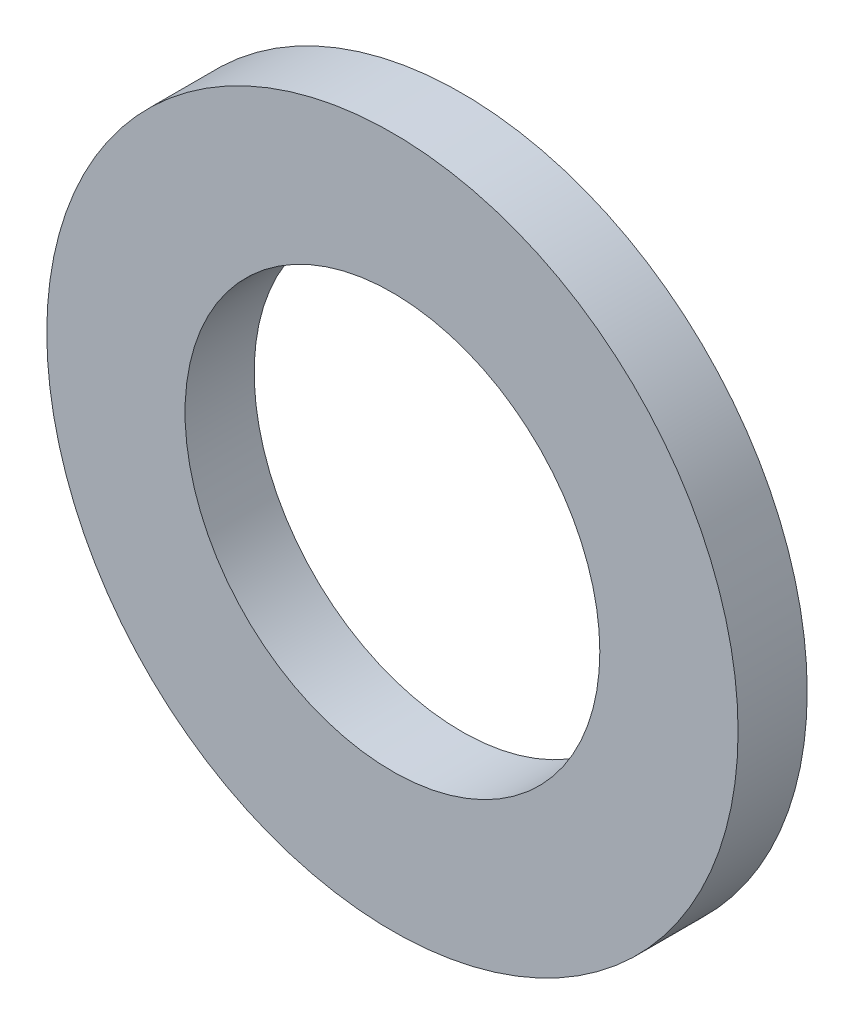
SolidWorks part; units mm, degrees
ref_plane "Plan1" through (0, 0, 0) normal (0, 0, 1) x (1, 0, 0)
ref_plane "Plan2" through (0, 0, 0) normal (0, 1, 0) x (1, 0, 0)
ref_plane "Plan3" through (0, 0, 0) normal (1, 0, 0) x (0, 0, -1)
sketch "Esquisse1" plane through (0, 0, 0) normal (0, 0, 1) x (1, 0, 0)
  circle A0 centre (0, 0) radius 10
  circle A1 centre (0, 0) radius 6
  dimension "D1" = 12
  dimension "D2" = 20
extrude "Base-Extrusion" add sketch "Esquisse1" along normal blind 2
